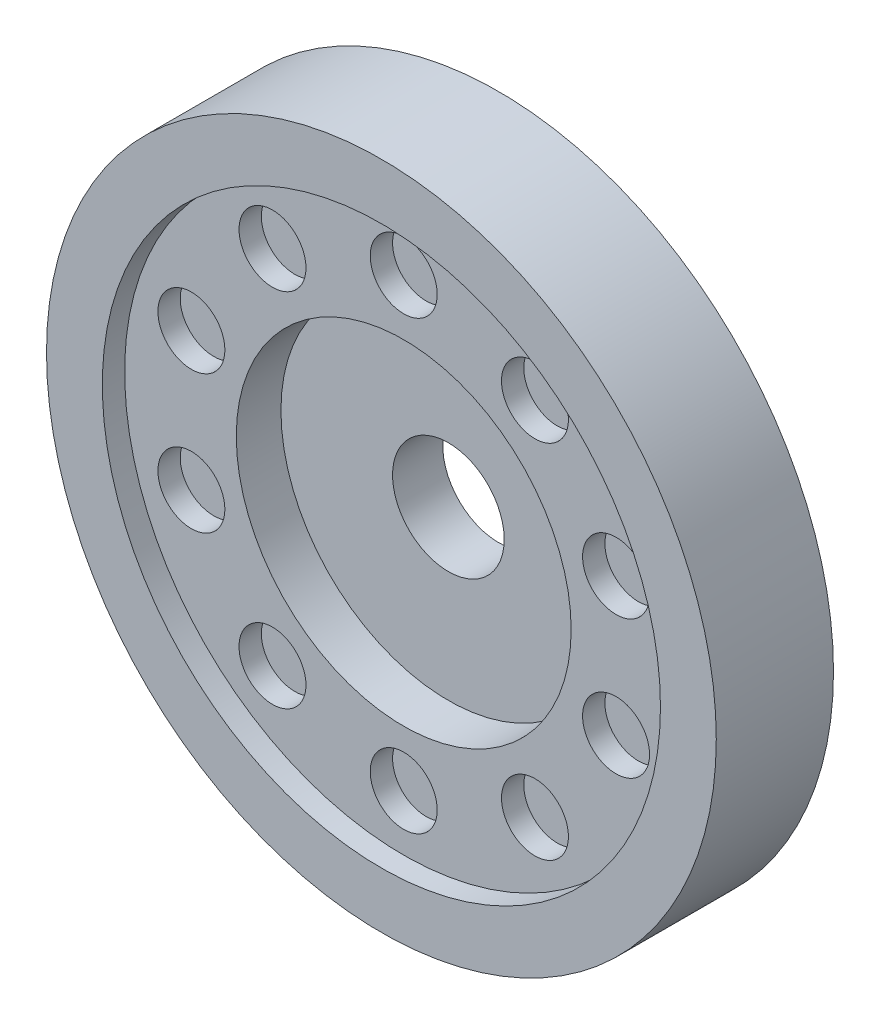
SolidWorks part; units mm, degrees
ref_plane "Front Plane" through (0, 0, 0) normal (0, 0, 1) x (1, 0, 0)
ref_plane "Top Plane" through (0, 0, 0) normal (0, 1, 0) x (1, 0, 0)
ref_plane "Right Plane" through (0, 0, 0) normal (1, 0, 0) x (0, 0, -1)
sketch "Sketch2" plane through (0, 0, 0) normal (0, 0, 1) x (1, 0, 0)
  circle A0 centre (0, 0) radius 381
  dimension "D1" = 762
extrude "Boss-Extrude1" add sketch "Sketch2" along normal blind 133.35
sketch "Sketch3" plane through (0, 0, 133.35) normal (0, 0, 1) x (1, 0, 0)
  circle A0 centre (0, 0) radius 317.5
  dimension "D1" = 635
extrude "Cut-Extrude1" cut sketch "Sketch3" against normal blind 25.4
sketch "Sketch4" plane through (0, 0, 107.95) normal (0, 0, 1) x (1, 0, 0)
  circle A0 centre (0, 0) radius 254 construction
  circle A1 centre (0, 254) radius 38.1
  circle A2 centre (149.2975, 205.4903) radius 38.1
  circle A3 centre (241.5684, 78.4903) radius 38.1
  circle A4 centre (241.5684, -78.4903) radius 38.1
  circle A5 centre (149.2975, -205.4903) radius 38.1
  circle A6 centre (0, -254) radius 38.1
  circle A7 centre (-149.2975, -205.4903) radius 38.1
  circle A8 centre (-241.5684, -78.4903) radius 38.1
  circle A9 centre (-241.5684, 78.4903) radius 38.1
  circle A10 centre (-149.2975, 205.4903) radius 38.1
  point P26 (0, 0)
  dimension "D1" = 508
  dimension "D2" = 76.2
  dimension "D3" = 10
extrude "Cut-Extrude2" cut sketch "Sketch4" against normal blind 25.4
sketch "Sketch5" plane through (0, 0, 107.95) normal (0, 0, 1) x (1, 0, 0)
  circle A0 centre (0, 0) radius 190.5
  point P3 (0, 0)
  dimension "D1" = 381
extrude "Cut-Extrude3" cut sketch "Sketch5" against normal blind 50.8
sketch "Sketch6" plane through (0, 0, 57.15) normal (0, 0, 1) x (1, 0, 0)
  circle A0 centre (0, 0) radius 63.5
  dimension "D1" = 127
extrude "Cut-Extrude4" cut sketch "Sketch6" against normal through all
